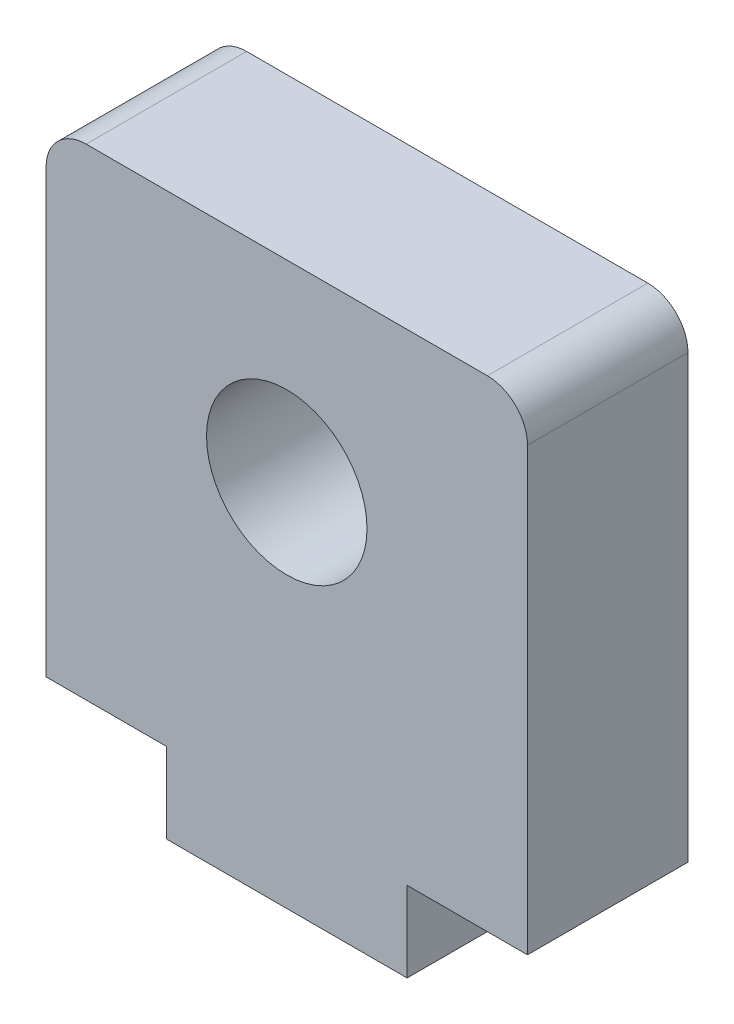
SolidWorks part; units mm, degrees
material "6061-T6 (SS)"
ref_plane "X-Y Datum" through (0, 0, 0) normal (0, 0, 1) x (1, 0, 0)
ref_plane "X-Z Datum" through (0, 0, 0) normal (0, 1, 0) x (1, 0, 0)
ref_plane "Y-Z Datum" through (0, 0, 0) normal (1, 0, 0) x (0, 0, -1)
sketch "Sketch1" plane through (0, 0, 0) normal (0, 0, 1) x (1, 0, 0)
  line L0 (0, 11.1125) -> (0, -11.1125) construction
  line L5 (-9.525, 11.1125) -> (9.525, 11.1125)
  line L6 (-9.525, 11.1125) -> (-9.525, -11.1125)
  line L7 (-9.525, -11.1125) -> (9.525, -11.1125)
  line L8 (9.525, 11.1125) -> (9.525, -11.1125)
  line L9 (-9.525, 11.1125) -> (9.525, -11.1125) construction
  line L10 (-9.525, -11.1125) -> (9.525, 11.1125) construction
  line L11 (-9.525, -7.9375) -> (9.525, -7.9375)
  line L12 (0, -7.9375) -> (0, -11.1125) construction
  line L14 (-4.7625, -7.9375) -> (4.7625, -7.9375)
  line L15 (-4.7625, -7.9375) -> (-4.7625, -11.1125)
  line L16 (-4.7625, -11.1125) -> (4.7625, -11.1125)
  line L17 (4.7625, -7.9375) -> (4.7625, -11.1125)
  line L18 (-4.7625, -7.9375) -> (4.7625, -11.1125) construction
  line L19 (-4.7625, -11.1125) -> (4.7625, -7.9375) construction
  circle A0 centre (0, 3.4925) radius 3.175
  point P0 (0, 0)
  point P14 (0, -9.525)
  dimension "D2" = 6.35
  dimension "D1" = 19.05
  dimension "D3" = 22.225
  dimension "D4" = 7.62
  dimension "D5" = 3.175
  dimension "D6" = 9.525
extrude "Boss-Extrude1" add sketch "Sketch1" along normal blind 6.35 contours L6 L11 L8 L5 A0 | L17 L11 L15 L7
fillet "Fillet1" radius 1.5875 2 edges at (9.525, 11.1125, 3.175) (-9.525, 11.1125, 3.175)
